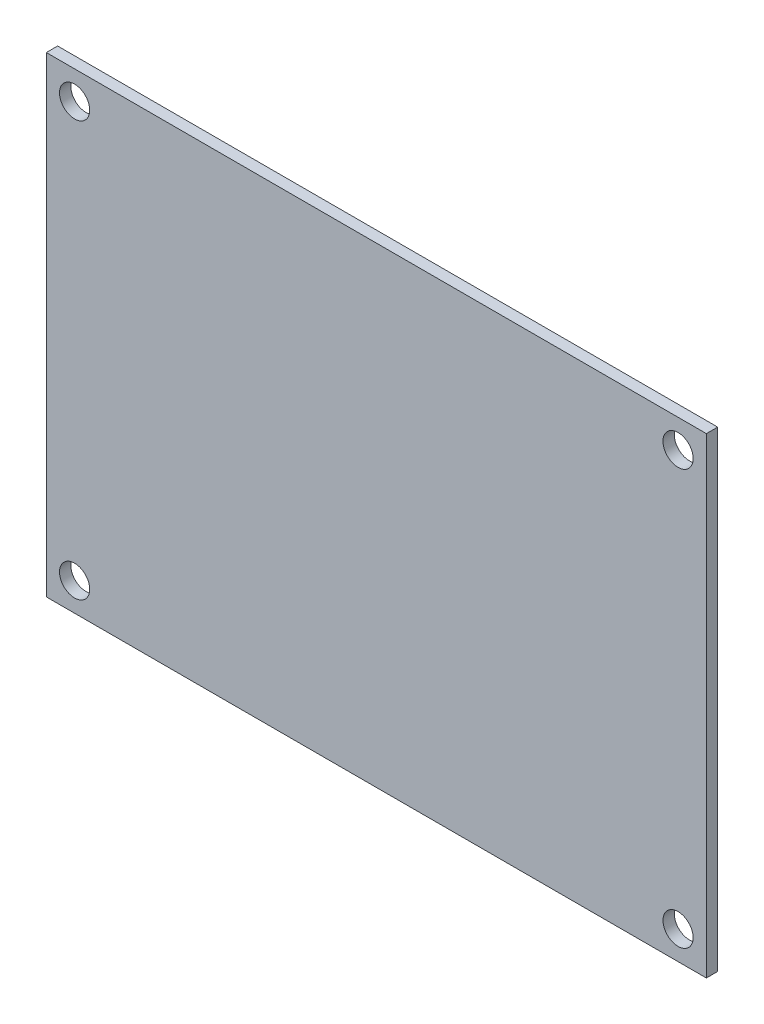
SolidWorks part; units mm, degrees
ref_plane "Front Plane" through (0, 0, 0) normal (0, 0, 1) x (1, 0, 0)
ref_plane "Top Plane" through (0, 0, 0) normal (0, 1, 0) x (1, 0, 0)
ref_plane "Right Plane" through (0, 0, 0) normal (1, 0, 0) x (0, 0, -1)
sketch "Sketch1" plane through (0, 0, 0) normal (0, 0, 1) x (1, 0, 0)
  line L1 (-35, -25) -> (35, -25)
  line L2 (-35, -25) -> (-35, 25)
  line L3 (-35, 25) -> (35, 25)
  line L4 (35, -25) -> (35, 25)
  line L5 (-35, -25) -> (35, 25) construction
  line L6 (-35, 25) -> (35, -25) construction
  point P1 (0, 0)
  dimension "D1" = 70
  dimension "D2" = 50
extrude "Boss-Extrude1" add sketch "Sketch1" along normal blind 1.2
sketch "Sketch6" plane through (0, 0, 1.2) normal (0, 0, 1) x (1, 0, 0)
  line L0 (0, -25) -> (0, 25) construction
  line L1 (-35, -25) -> (35, -25) construction
  line L2 (35, 25) -> (-35, 25) construction
  line L3 (-35, 0) -> (35, 0) construction
  line L4 (-35, 25) -> (-35, -25) construction
  line L5 (35, -25) -> (35, 25) construction
  line L6 (-32, 23) -> (32, 23) construction
  line L7 (-32, -23) -> (32, -23) construction
  line L8 (-33, -22) -> (-33, 22) construction
  line L9 (33, 22) -> (33, -22) construction
  circle A0 centre (-32, 22) radius 1 construction
  circle A1 centre (-32, -22) radius 1 construction
  circle A2 centre (32, 22) radius 1 construction
  circle A3 centre (32, -22) radius 1 construction
  circle A4 centre (-32, -22) radius 1.6
  circle A5 centre (32, -22) radius 1.6
  circle A6 centre (32, 22) radius 1.6
  circle A7 centre (-32, 22) radius 1.6
  dimension "D3" = 2
  dimension "D4" = 3.2
  dimension "D1" = 66
  dimension "D2" = 46
extrude "Cut-Extrude1" cut sketch "Sketch6" against normal up to next
